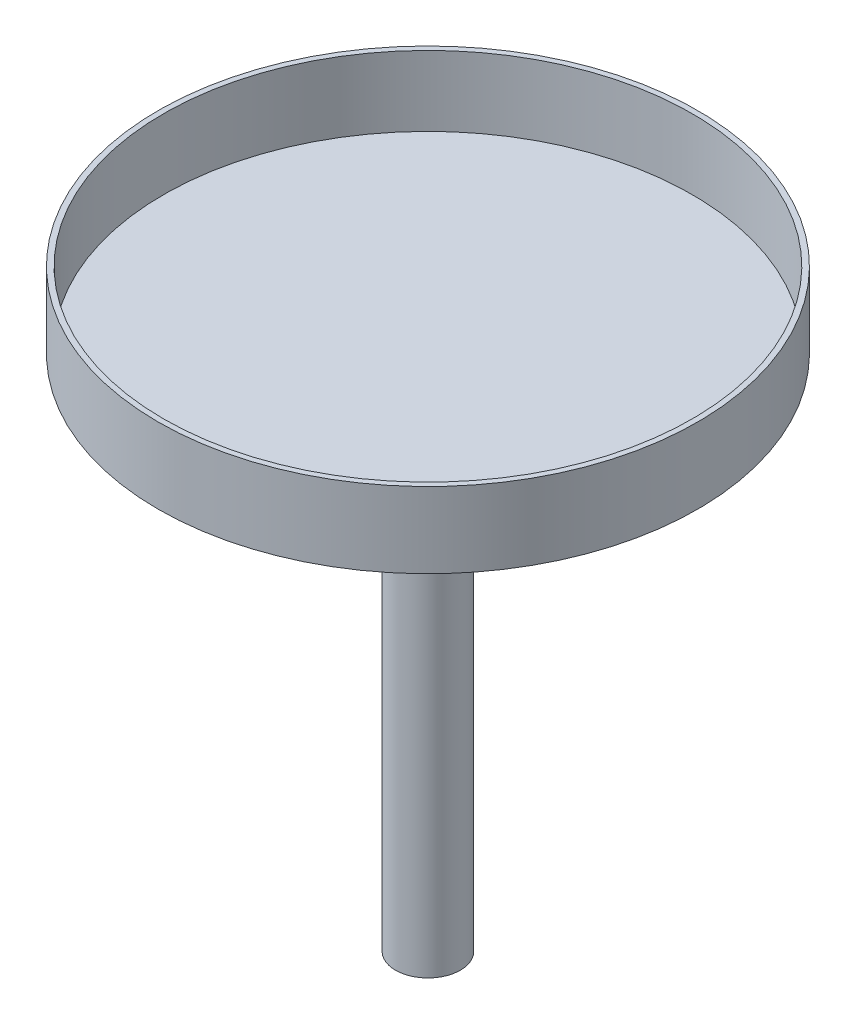
SolidWorks part; units mm, degrees
ref_plane "Front Plane" through (0, 0, 0) normal (0, 0, 1) x (1, 0, 0)
ref_plane "Top Plane" through (0, 0, 0) normal (0, 1, 0) x (1, 0, 0)
ref_plane "Right Plane" through (0, 0, 0) normal (1, 0, 0) x (0, 0, -1)
sketch "Sketch1" plane through (0, 0, 0) normal (0, 0, 1) x (1, 0, 0)
  line L0 (0, 40.9286) -> (0, -50.3571) construction
  line L1 (30, -480) -> (30, 0)
  line L2 (30, 0) -> (250, 0)
  line L3 (250, 0) -> (250, 70)
  line L4 (250, 70) -> (245, 70)
  line L5 (245, 70) -> (245, 5)
  line L6 (245, 5) -> (0, 5)
  line L7 (0, 5) -> (0, -480)
  line L8 (0, -480) -> (30, -480)
  dimension "D1" = 5
  dimension "D2" = 5
  dimension "D3" = 70
  dimension "D4" = 30
  dimension "D5" = 250
  dimension "D6" = 550
revolve "Revolve1" add sketch "Sketch1" angle 360 about L0
